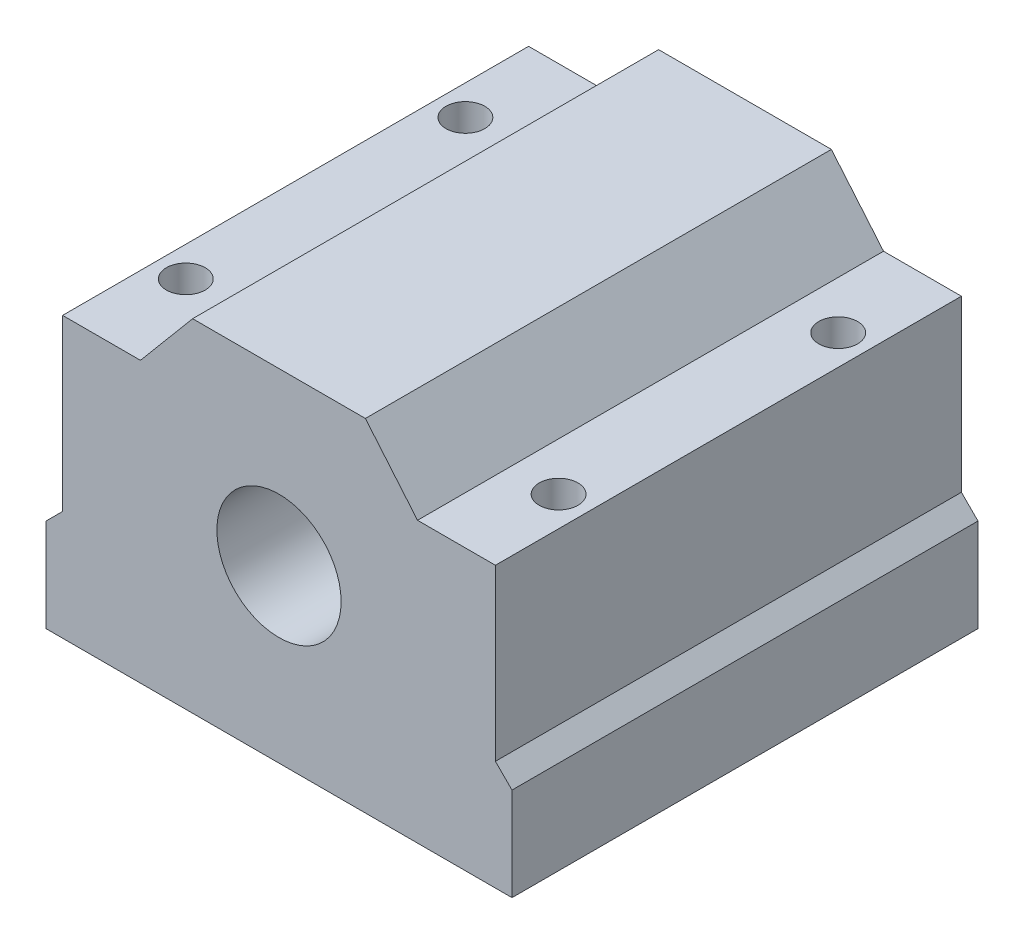
SolidWorks part; units mm, degrees
ref_plane "Front Plane" through (0, 0, 0) normal (0, 0, 1) x (1, 0, 0)
ref_plane "Top Plane" through (0, 0, 0) normal (0, 1, 0) x (1, 0, 0)
ref_plane "Right Plane" through (0, 0, 0) normal (1, 0, 0) x (0, 0, -1)
sketch "Sketch1" plane through (0, 0, 0) normal (0, 0, 1) x (1, 0, 0)
  line L0 (0, 0) -> (36.3993, 0) construction
  line L1 (0, 0) -> (0, 38.3981) construction
  line L2 (0, 0) -> (0, -13.4067) construction
  line L3 (0, 0) -> (-20.6819, 0) construction
  line L4 (-15, -11) -> (15, -11)
  line L5 (15, -11) -> (15, -5)
  line L6 (15, -5) -> (13.9317, -3.9317)
  line L7 (13.9317, -3.9317) -> (13.9317, 7)
  line L8 (13.9317, 7) -> (8.9177, 7)
  line L9 (8.9177, 7) -> (5.5613, 11)
  line L10 (5.5613, 11) -> (-5.5613, 11)
  line L11 (-15, -11) -> (-15, -5)
  line L12 (-15, -5) -> (-13.9317, -3.9317)
  line L13 (-13.9317, -3.9317) -> (-13.9317, 7)
  line L14 (-13.9317, 7) -> (-8.9177, 7)
  line L15 (-8.9177, 7) -> (-5.5613, 11)
  circle A0 centre (0, 0) radius 4
  point P9 (0, 0)
  point P16 (0, 0)
  point P17 (0, 0)
  point P18 (0, 0)
  point P19 (0, 0)
  point P20 (0, 0)
  point P21 (0, 0)
  point P22 (0, 0)
  point P23 (0, 0)
  point P25 (0, -11)
  point P30 (0, 11)
  dimension "D1" = 8
  dimension "D2" = 15
  dimension "D3" = 22
  dimension "D4" = 18
  dimension "D5" = 6
  dimension "D6" = 45
  dimension "D7" = 50
  dimension "D8" = 11
extrude "Boss-Extrude1" add sketch "Sketch1" against normal blind 30
sketch "Sketch2" plane through (0, 0, 0) normal (0, 1, 0) x (1, 0, 0)
  line L0 (0, 0) -> (0, 31.1735) construction
  line L1 (-16.5501, 15) -> (20.037, 15) construction
  point P3 (-12, 6)
  point P4 (-12, 24)
  point P7 (0, 0)
  point P8 (0, 0)
  point P9 (12, 6)
  point P10 (12, 24)
  point P11 (0, 0)
  dimension "D1" = 12
  dimension "D2" = 9
  dimension "D3" = 15
  dimension "D4" = 9
sketch "Sketch3" plane through (0, 7, 0) normal (0, 1, 0) x (1, 0, 0)
  point P0 (-12, 24)
  point P3 (-12, 6)
  point P6 (12, 6)
  point P9 (12, 24)
hole_wizard "Ø2.5mm Dowel Hole1" positions "Sketch3" profile "Sketch5" hole size "Ø2.5" standard "ANSI Metric" end condition through all
sketch "Sketch5" plane through (-12, 7, -24) normal (1, 0, 0) x (0, 0, 1)
  line L0 (0, 0) -> (0, 18)
  line L1 (0, 18) -> (1.25, 18)
  line L2 (1.25, 18) -> (1.25, 0)
  line L5 (1.25, 0) -> (0, 0)
  line L11 (0, -6.35) -> (0, 107.95) construction
  dimension "Thru Hole Dia." = 2.5
  dimension "Thru Hole Depth" = 18
